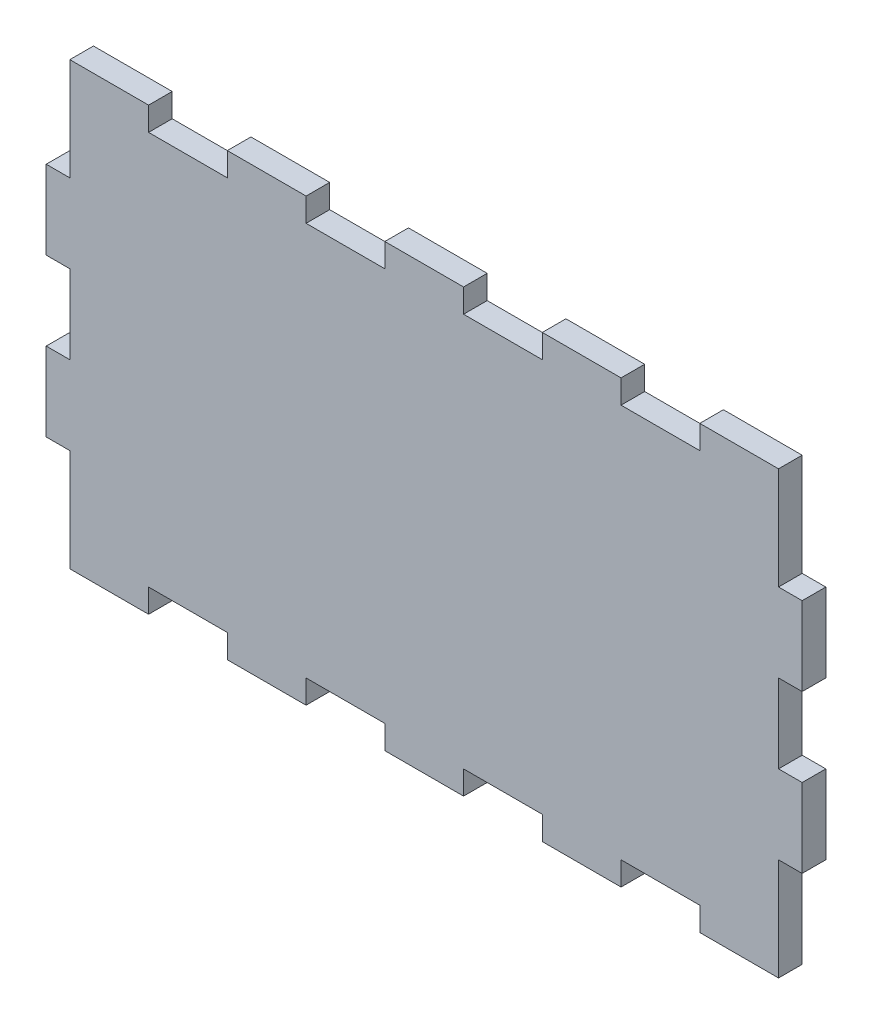
SolidWorks part; units mm, degrees
ref_plane "Front Plane" through (0, 0, 0) normal (0, 0, 1) x (1, 0, 0)
ref_plane "Top Plane" through (0, 0, 0) normal (0, 1, 0) x (1, 0, 0)
ref_plane "Right Plane" through (0, 0, 0) normal (1, 0, 0) x (0, 0, -1)
sketch "Sketch1" plane through (0, 0, 0) normal (0, 0, 1) x (1, 0, 0)
  line L0 (25, 28) -> (25, 25)
  line L1 (-46.5, 26.5) -> (46.5, 26.5) construction
  line L2 (-46.5, 26.5) -> (-46.5, -26.5) construction
  line L3 (-46.5, -26.5) -> (46.5, -26.5) construction
  line L4 (46.5, 26.5) -> (46.5, -26.5) construction
  line L5 (-46.5, 26.5) -> (46.5, -26.5) construction
  line L6 (-46.5, -26.5) -> (46.5, 26.5) construction
  line L7 (-5, 28) -> (5, 28)
  line L8 (-5, 28) -> (-5, 25)
  line L9 (-5, 25) -> (5, 25) construction
  line L10 (5, 28) -> (5, 25)
  line L11 (-5, 28) -> (5, 25) construction
  line L12 (-5, 25) -> (5, 28) construction
  line L13 (15, 28) -> (25, 28)
  line L14 (15, 28) -> (15, 25)
  line L15 (45, 28) -> (45, 25)
  line L16 (35, 28) -> (45, 28)
  line L17 (35, 28) -> (35, 25)
  line L18 (-15, 28) -> (-15, 25)
  line L19 (-25, 28) -> (-15, 28)
  line L20 (-25, 28) -> (-25, 25)
  line L21 (-35, 28) -> (-35, 25)
  line L22 (-45, 28) -> (-35, 28)
  line L23 (0, 0) -> (8.5024, 0) construction
  line L24 (-45, 28) -> (-45, 25)
  line L25 (-35, 25) -> (-25, 25)
  line L26 (-15, 25) -> (-5, 25)
  line L27 (5, 25) -> (15, 25)
  line L28 (0, 0) -> (0, 11.5614) construction
  line L29 (25, 25) -> (35, 25)
  line L30 (-48, 5) -> (-48, 15)
  line L31 (-48, -15) -> (-45, -15)
  line L32 (-45, -15) -> (-45, -25)
  line L33 (-48, -15) -> (-48, -5)
  line L34 (45, -28) -> (45, -25)
  line L35 (35, -28) -> (45, -28)
  line L36 (35, -28) -> (35, -25)
  line L37 (25, -25) -> (35, -25)
  line L38 (25, -28) -> (25, -25)
  line L39 (15, -28) -> (15, -25)
  line L40 (15, -28) -> (25, -28)
  line L41 (5, -25) -> (15, -25)
  line L42 (5, -28) -> (5, -25)
  line L43 (-5, -28) -> (5, -28)
  line L44 (-5, -28) -> (-5, -25)
  line L45 (-15, -25) -> (-5, -25)
  line L46 (-15, -28) -> (-15, -25)
  line L47 (-25, -28) -> (-15, -28)
  line L48 (-48, 5) -> (-45, 5)
  line L49 (-48, 5) -> (-48, -5) construction
  line L50 (-48, -5) -> (-45, -5)
  line L51 (-45, 5) -> (-45, -5)
  line L52 (-48, 5) -> (-45, -5) construction
  line L53 (-48, -5) -> (-45, 5) construction
  line L54 (-45, 25) -> (-45, 15)
  line L55 (-48, 15) -> (-45, 15)
  line L56 (-48, 25) -> (-45, 25) [skipped]
  line L57 (-25, -28) -> (-25, -25)
  line L58 (-35, -28) -> (-35, -25)
  line L59 (-35, -25) -> (-25, -25)
  line L60 (-45, -28) -> (-35, -28)
  line L61 (45, -15) -> (45, -25)
  line L62 (48, -15) -> (45, -15)
  line L63 (48, -15) -> (48, -5)
  line L64 (48, -5) -> (45, -5)
  line L65 (45, 5) -> (45, -5)
  line L66 (48, 5) -> (45, 5)
  line L67 (-48, -25) -> (-45, -25) [skipped]
  line L68 (48, 5) -> (48, 15)
  line L69 (48, 15) -> (45, 15)
  line L70 (45, 25) -> (45, 15)
  line L71 (-45, -28) -> (-45, -25)
  point P0 (0, 0)
  point P6 (0, 26.5)
  point P50 (-46.5, 0)
  dimension "D1" = 93
  dimension "D2" = 53
  dimension "D3" = 10
  dimension "D4" = 3
  dimension "D8" = 3
  dimension "D9" = 10
  dimension "D10" = 3
  dimension "D7" = 3
  dimension "D11" = 2
  dimension "D5" = 2
extrude "Boss-Extrude1" add sketch "Sketch1" along normal blind 3
